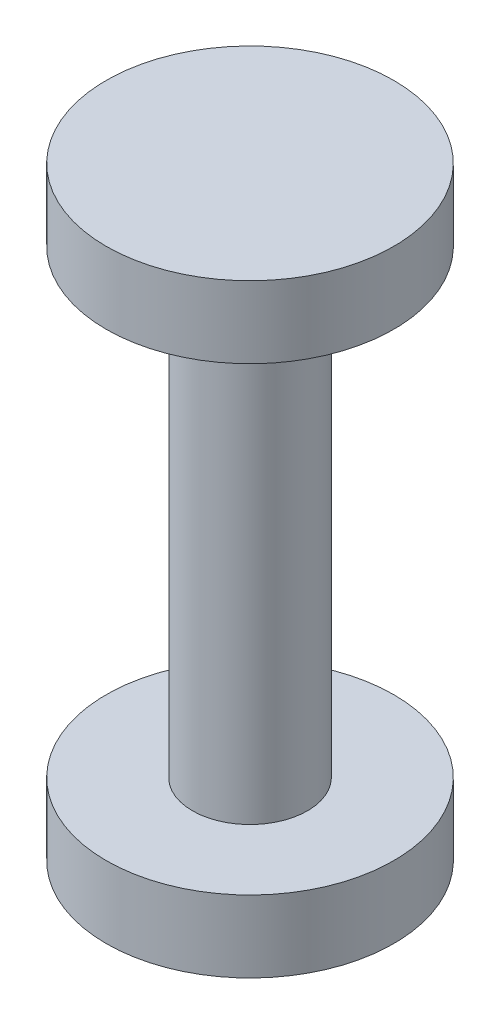
SolidWorks part; units mm, degrees
ref_plane "Front Plane" through (0, 0, 0) normal (0, 0, 1) x (1, 0, 0)
ref_plane "Top Plane" through (0, 0, 0) normal (0, 1, 0) x (1, 0, 0)
ref_plane "Right Plane" through (0, 0, 0) normal (1, 0, 0) x (0, 0, -1)
sketch "Sketch1" plane through (0, 0, 0) normal (0, 0, 1) x (1, 0, 0)
  line L0 (0, 10.668) -> (0, 0)
  line L1 (0, -55) -> (0, 55) construction
  line L2 (0, 0) -> (2.54, 0)
  line L3 (55, 0) -> (-55, 0) construction
  line L4 (2.54, 0) -> (2.54, 1.27)
  line L5 (2.54, 1.27) -> (1.016, 1.27)
  line L6 (1.016, 1.27) -> (1.016, 9.398)
  line L7 (1.016, 5.334) -> (0, 5.334) construction
  line L8 (2.54, 9.398) -> (1.016, 9.398)
  line L9 (2.54, 10.668) -> (2.54, 9.398)
  line L10 (0, 10.668) -> (2.54, 10.668)
  dimension "D1" = 1.016
  dimension "D2" = 4.064
  dimension "D3" = 1.27
  dimension "D4" = 2.54
revolve "Revolve1" add sketch "Sketch1" angle 360 about L0
